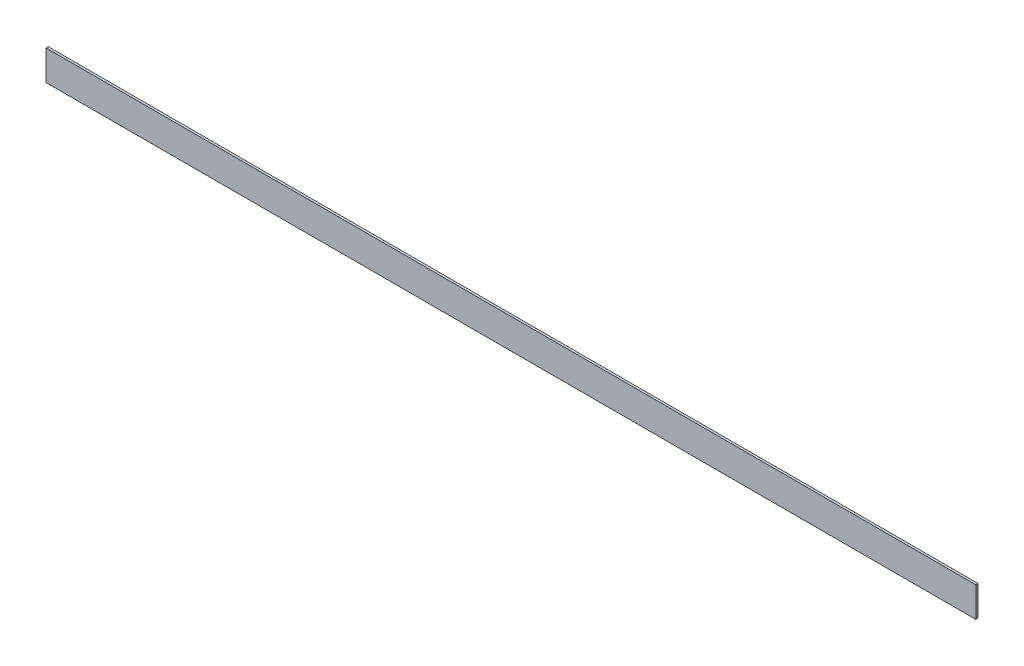
SolidWorks part; units mm, degrees
ref_plane "Front Plane" through (0, 0, 0) normal (0, 0, 1) x (1, 0, 0)
ref_plane "Top Plane" through (0, 0, 0) normal (0, 1, 0) x (1, 0, 0)
ref_plane "Right Plane" through (0, 0, 0) normal (1, 0, 0) x (0, 0, -1)
other "Configuration Table"
sketch "Sketch1" plane through (0, 0, 0) normal (0, 0, 1) x (1, 0, 0)
  line L1 (40, 1132) -> (660, 1132)
  line L2 (40, 1132) -> (40, 1152)
  line L3 (40, 1152) -> (660, 1152)
  line L4 (660, 1132) -> (660, 1152)
extrude "PRESS_uc_rafi_raf_buk_arka_1" add sketch "Sketch1" against normal blind 1.5 from offset 798.5 separate body
